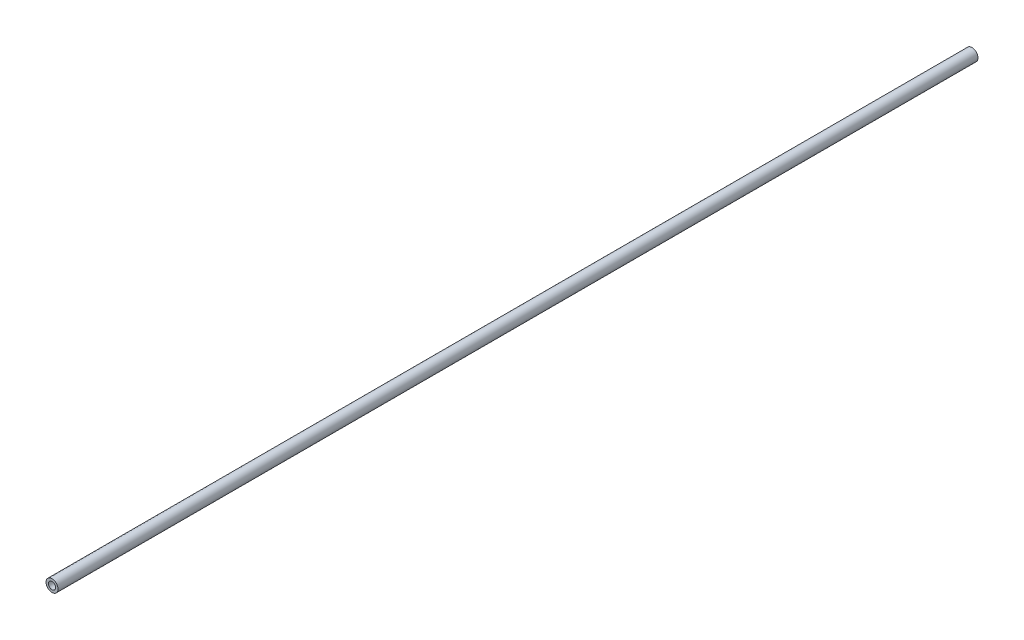
SolidWorks part; units mm, degrees
ref_plane "Front" through (0, 0, 0) normal (0, 0, 1) x (1, 0, 0)
ref_plane "Top" through (0, 0, 0) normal (0, 1, 0) x (1, 0, 0)
ref_plane "Right" through (0, 0, 0) normal (1, 0, 0) x (0, 0, -1)
sketch "Sketch1" plane through (0, 0, 0) normal (1, 0, 0) x (0, 0, -1)
  line L0 (-152.4, 0) -> (152.4, 0) construction
  line L1 (-152.4, 1.9844) -> (152.4, 1.9844)
  line L2 (-152.4, 1.9844) -> (-152.4, 1.1906)
  line L3 (-152.4, 1.1906) -> (152.4, 1.1906)
  line L4 (152.4, 1.9844) -> (152.4, 1.1906)
  point P4 (148.4313, 1.9844)
  point P8 (0, 0)
  point P11 (-148.4313, 1.9844)
  dimension "Length (Representative, 25ft)" = 304.8
  dimension "ID" = 2.3813
  dimension "OD" = 3.9688
  dimension "D1" = 3.9688
  dimension "D2" = 3.9688
sketch "Sketch2" plane through (0, 0, 0) normal (1, 0, 0) x (0, 0, -1)
  line L0 (-152.4, 1.9844) -> (152.4, 1.9844) construction
  line L1 (152.4, 1.9844) -> (152.4, 1.1906) construction
  line L2 (-152.4, 1.1906) -> (152.4, 1.1906) construction
  line L3 (-152.4, 1.9844) -> (-152.4, 1.1906) construction
  line L4 (-152.4, 1.9844) -> (152.4, 1.9844)
  line L5 (152.4, 1.9844) -> (152.4, 1.1906)
  line L6 (-152.4, 1.1906) -> (152.4, 1.1906)
  line L7 (-152.4, 1.9844) -> (-152.4, 1.1906)
  line L8 (-152.4, 0) -> (152.4, 0) construction
  line L9 (-152.4, 0) -> (152.4, 0) construction
revolve "Revolve1" add sketch "Sketch2" angle 360 about L9
equation "\"D1@Sketch1\"=\"OD@Sketch1\""
equation "\"D2@Sketch1\"=\"D1@Sketch1\""
